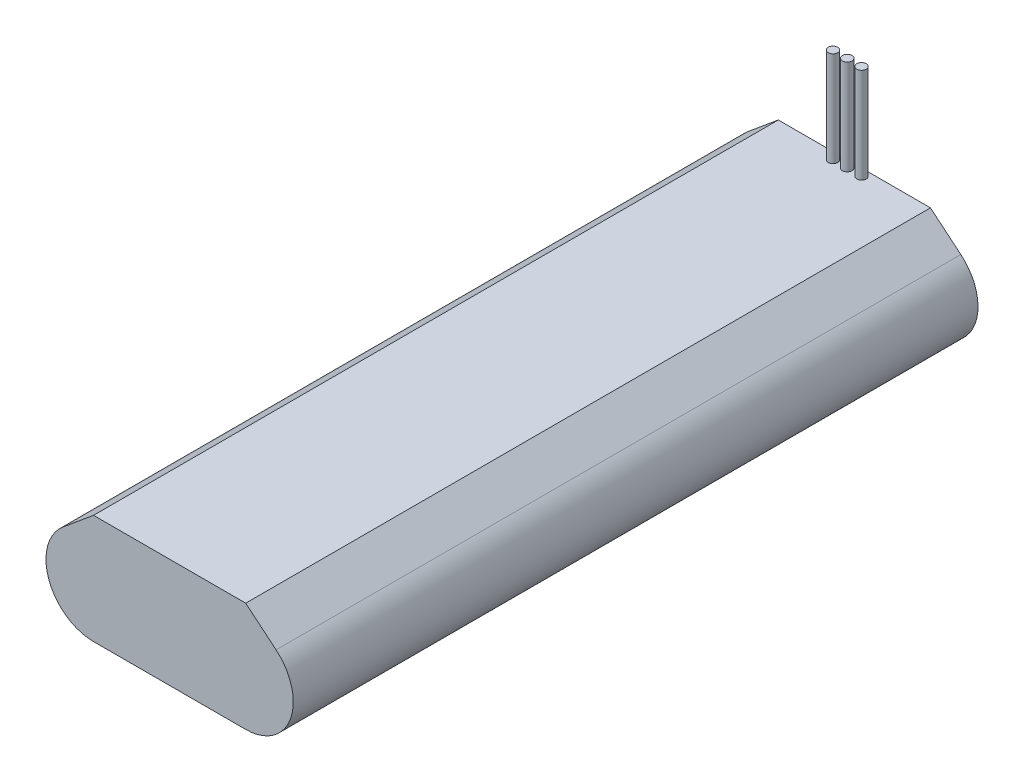
SolidWorks part; units mm, degrees
ref_plane "정면" through (0, 0, 0) normal (0, 0, 1) x (1, 0, 0)
ref_plane "윗면" through (0, 0, 0) normal (0, 1, 0) x (1, 0, 0)
ref_plane "우측면" through (0, 0, 0) normal (1, 0, 0) x (0, 0, -1)
sketch "스케치1" plane through (0, 0, 0) normal (0, 0, 1) x (1, 0, 0)
  line L0 (-16, 0) -> (16, 0) construction
  line L2 (-16, -10) -> (16, -10)
  line L3 (-16, 13) -> (-22.3897, 7.6923)
  line L6 (-16, 13) -> (16, 13)
  line L8 (16, 13) -> (22.3897, 7.6923)
  arc A0 (-22.3897, 7.6923) -> (-16, -10) centre (-16, 0) ccw
  arc A1 (16, -10) -> (22.3897, 7.6923) centre (16, 0) ccw
  point P3 (0, 0)
  dimension "D2" = 32
extrude "보스-돌출1" add sketch "스케치1" along normal blind 144
sketch "스케치2" plane through (0, 13, 0) normal (0, 1, 0) x (1, 0, 0)
  line L0 (16, 0) -> (-16, 0) construction
  line L1 (0, 0) -> (0, -5.5326) construction
  circle A0 centre (-3, -1.5) radius 1
  circle A1 centre (0, -1.5) radius 1
  circle A2 centre (3, -1.5) radius 1
  dimension "D1" = 2
  dimension "D2" = 3
  dimension "D3" = 3
  dimension "D4" = 1.5
  dimension "D5" = 1.5
  dimension "D6" = 1.5
extrude "보스-돌출2" add sketch "스케치2" along normal blind 20
